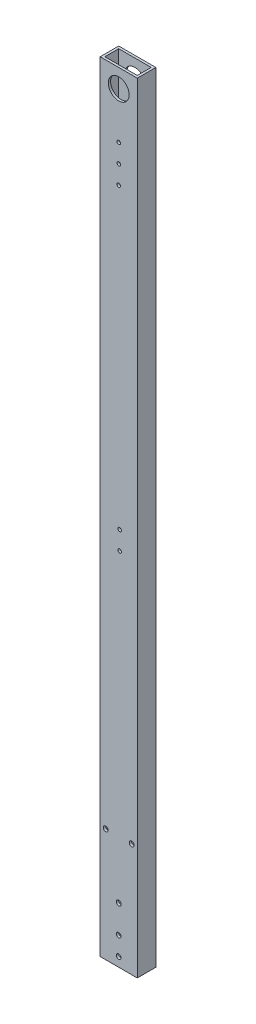
SolidWorks part; units mm, degrees
material "5052-O"
ref_plane "Front Plane" through (0, 0, 0) normal (0, 0, 1) x (1, 0, 0)
ref_plane "Top Plane" through (0, 0, 0) normal (0, 1, 0) x (1, 0, 0)
ref_plane "Right Plane" through (0, 0, 0) normal (1, 0, 0) x (0, 0, -1)
sketch "Sketch1" plane through (0, 0, 0) normal (0, 1, 0) x (1, 0, 0)
  line L0 (-22.225, 9.525) -> (22.225, 9.525)
  line L1 (-25.4, -12.7) -> (25.4, -12.7)
  line L2 (-25.4, -12.7) -> (-25.4, 12.7)
  line L3 (-25.4, 12.7) -> (25.4, 12.7)
  line L4 (25.4, -12.7) -> (25.4, 12.7)
  line L5 (-25.4, -12.7) -> (25.4, 12.7) construction
  line L6 (-25.4, 12.7) -> (25.4, -12.7) construction
  line L7 (22.225, -9.525) -> (22.225, 9.525)
  line L8 (-22.225, -9.525) -> (22.225, -9.525)
  line L9 (-22.225, -9.525) -> (-22.225, 9.525)
  point P0 (0, 0)
  dimension "D1" = 25.4
  dimension "D2" = 50.8
  dimension "D3" = 3.175
extrude "Boss-Extrude1" add sketch "Sketch1" along normal blind 1066.8
sketch "Sketch2" plane through (0, 0, 12.7) normal (0, 0, 1) x (1, 0, 0)
  line L0 (-25.4, 1066.8) -> (25.4, 1066.8) construction
  line L1 (0, 1041.4) -> (0, 1066.8) construction
  circle A0 centre (0, 1041.4) radius 14.2875
  dimension "D1" = 28.575
  dimension "D2" = 25.4
extrude "Cut-Extrude1" cut sketch "Sketch2" against normal through all
sketch "Sketch3" plane through (0, 0, 12.7) normal (0, 0, 1) x (1, 0, 0)
  line L0 (0, 38.1) -> (0, 0) construction
  line L1 (-25.4, 0) -> (25.4, 0) construction
  circle A0 centre (0, 12.7) radius 3.175
  circle A1 centre (0, 38.1) radius 3.175
  dimension "D1" = 6.35
  dimension "D2" = 6.35
  dimension "D3" = 12.7
  dimension "D4" = 25.4
extrude "Cut-Extrude2" cut sketch "Sketch3" against normal through all
sketch "Sketch4" plane through (0, 0, 12.7) normal (0, 0, 1) x (1, 0, 0)
  circle A0 centre (0, 977.9) radius 2.4638
  circle A1 centre (0, 952.5) radius 2.4638
  circle A2 centre (0, 927.1) radius 2.4638
  circle A3 centre (1.27, 519.5854) radius 2.4638
  circle A4 centre (1.27, 494.1854) radius 2.4638
  dimension "D1" = 4.9276
extrude "Cut-Extrude3" cut sketch "Sketch4" against normal through all
sketch "Sketch5" plane through (0, 0, 12.7) normal (0, 0, 1) x (1, 0, 0)
  line L0 (-25.4, 0) -> (25.4, 0) construction
  circle A0 centre (0, 76.2) radius 3.3734
  dimension "D1" = 6.7469
  dimension "D2" = 76.2
extrude "Cut-Extrude4" cut sketch "Sketch5" against normal through all
sketch "Sketch6" plane through (0, 0, 12.7) normal (0, 0, 1) x (1, 0, 0)
  circle A0 centre (-17.78, 155.1754) radius 3.3734
  circle A1 centre (17.78, 155.1754) radius 3.3734
extrude "Cut-Extrude5" cut sketch "Sketch6" against normal through all
sketch "Sketch7" plane through (0, 0, 12.7) normal (0, 0, 1) x (1, 0, 0)
  line L0 (0, 0) -> (0, 1066.8) construction
  line L1 (-25.4, 1066.8) -> (25.4, 1066.8) construction
  line L2 (-25.4, 0) -> (25.4, 0) construction
  circle A0 centre (0, 114.3) radius 2.5797
  circle A1 centre (0, 254) radius 2.5797
  dimension "D1" = 5.1594
  dimension "D2" = 5.1594
  dimension "D3" = 114.3
  dimension "D4" = 139.7
